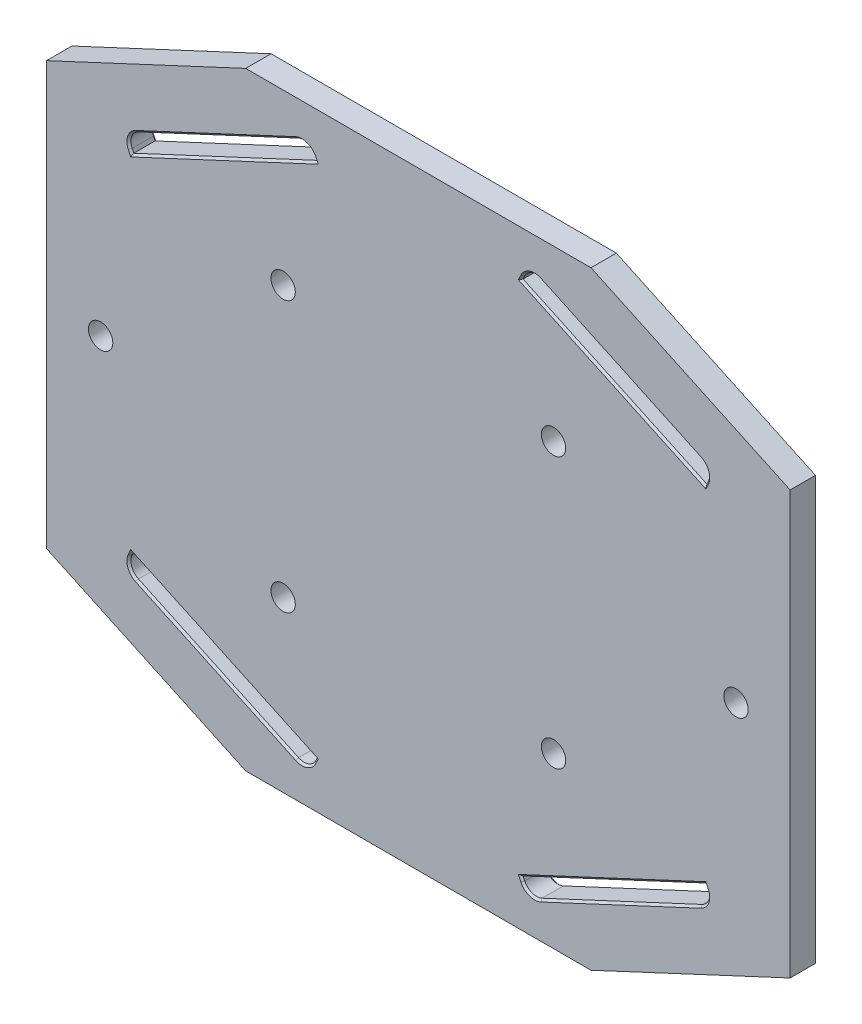
SolidWorks part; units mm, degrees
ref_plane "Front Plane" through (0, 0, 0) normal (0, 0, 1) x (1, 0, 0)
ref_plane "Top Plane" through (0, 0, 0) normal (0, 1, 0) x (1, 0, 0)
ref_plane "Right Plane" through (0, 0, 0) normal (1, 0, 0) x (0, 0, -1)
sketch "Sketch3" plane through (0, 0, 0) normal (0, 0, 1) x (1, 0, 0)
  line L0 (0, 114.3) -> (0, -114.3) construction
  line L1 (64.8681, -114.3) -> (-64.8681, -114.3)
  line L2 (139.7, -79.4053) -> (139.7, 79.4053)
  line L3 (64.8681, 114.3) -> (-64.8681, 114.3)
  line L4 (-139.7, -79.4053) -> (-139.7, 79.4053)
  line L5 (112.5338, -92.0731) -> (-112.5338, 92.0731) construction
  line L6 (112.5338, 92.0731) -> (-112.5338, -92.0731) construction
  line L7 (-9.2742, 114.3) -> (-139.7, 53.4814) construction
  line L8 (-139.7, 0) -> (139.7, 0) construction
  line L9 (9.2742, 114.3) -> (139.7, 53.4814) construction
  line L10 (9.2742, -114.3) -> (139.7, -53.4814) construction
  line L11 (-9.2742, -114.3) -> (-139.7, -53.4814) construction
  line L12 (-107.6756, 64.9114) -> (-38.6149, 97.1149)
  line L13 (-107.6756, 64.9114) -> (-110.3592, 70.6665)
  line L14 (-38.6149, 97.1149) -> (-41.2986, 102.87)
  line L15 (-110.3592, 70.6665) -> (-41.2986, 102.87)
  line L16 (-107.6756, 64.9114) -> (-41.2986, 102.87) construction
  line L17 (-38.6149, 97.1149) -> (-110.3592, 70.6665) construction
  line L18 (-102.284, 96.8526) -> (-74.4871, 83.8907) construction
  line L19 (38.6149, 97.1149) -> (41.2986, 102.87)
  line L20 (110.3592, 70.6665) -> (41.2986, 102.87)
  line L21 (107.6756, 64.9114) -> (110.3592, 70.6665)
  line L22 (107.6756, 64.9114) -> (38.6149, 97.1149)
  line L23 (-38.6149, -97.1149) -> (-41.2986, -102.87)
  line L24 (-110.3592, -70.6665) -> (-41.2986, -102.87)
  line L25 (-107.6756, -64.9114) -> (-110.3592, -70.6665)
  line L26 (-107.6756, -64.9114) -> (-38.6149, -97.1149)
  line L27 (107.6756, -64.9114) -> (38.6149, -97.1149)
  line L28 (107.6756, -64.9114) -> (110.3592, -70.6665)
  line L29 (110.3592, -70.6665) -> (41.2986, -102.87)
  line L30 (38.6149, -97.1149) -> (41.2986, -102.87)
  line L31 (64.8681, 114.3) -> (139.7, 79.4053)
  line L32 (-64.8681, 114.3) -> (-139.7, 79.4053)
  line L33 (64.8681, -114.3) -> (139.7, -79.4053)
  line L34 (-64.8681, -114.3) -> (-139.7, -79.4053)
  line L36 (50.8, -50.8) -> (-50.8, -50.8) construction
  line L37 (50.8, -50.8) -> (50.8, 50.8) construction
  line L38 (50.8, 50.8) -> (-50.8, 50.8) construction
  line L39 (-50.8, -50.8) -> (-50.8, 50.8) construction
  line L40 (50.8, -50.8) -> (-50.8, 50.8) construction
  line L41 (50.8, 50.8) -> (-50.8, -50.8) construction
  circle A0 centre (-50.8, 50.8) radius 4.572
  circle A1 centre (50.8, 50.8) radius 4.572
  circle A2 centre (50.8, -50.8) radius 4.572
  circle A3 centre (-50.8, -50.8) radius 4.572
  circle A4 centre (-119.38, 0) radius 4.572
  circle A5 centre (119.38, 0) radius 4.572
  point P0 (0, 0)
  point P4 (0, 0)
  point P19 (-74.4871, 83.8907)
  point P39 (102.284, 96.8526)
  dimension "D14" = 9.144
  dimension "D15" = 9.144
  dimension "D16" = 9.144
  dimension "D17" = 9.144
  dimension "D18" = 9.144
  dimension "D2" = 279.4
  dimension "D3" = 25
  dimension "D4" = 11.43
  dimension "D5" = 65
  dimension "D6" = 76.2
  dimension "D7" = 6.35
  dimension "D8" = 180
  dimension "D9" = 65
  dimension "D10" = 20.32
  dimension "D11" = 228.6
  dimension "D12" = 101.6
  dimension "D13" = 101.6
  dimension "D19" = 20.32
extrude "Boss-Extrude1" add sketch "Sketch3" along normal blind 9.525
fillet "Fillet1" radius 4.92 1 edges at (-41.2986, 102.87, 4.7625)
fillet "Fillet2" radius 4.92 1 edges at (-110.3592, 70.6665, 4.7625)
chamfer "Chamfer1" distance 0.762 6 edges at (-75.8289, 86.7682, 9.525) (-108.4442, 69.9695, 9.525) (-107.9778, 65.5594, 9.525) (-73.1453, 81.0132, 9.525) (-38.9171, 97.763, 9.525) (-41.9956, 100.955, 9.525)
chamfer "Chamfer2" distance 0.762 6 edges at (-38.9171, 97.763, 0) (-41.9956, 100.955, 0) (-73.1453, 81.0132, 0) (-107.9778, 65.5594, 0) (-108.4442, 69.9695, 0) (-75.8289, 86.7682, 0)
fillet "Fillet3" radius 4.92 1 edges at (41.2986, 102.87, 4.7625)
fillet "Fillet4" radius 4.92 1 edges at (110.3592, 70.6665, 4.7625)
fillet "Fillet5" radius 4.92 1 edges at (110.3592, -70.6665, 4.7625)
fillet "Fillet6" radius 4.92 1 edges at (41.2986, -102.87, 4.7625)
fillet "Fillet7" radius 4.92 1 edges at (-41.2986, -102.87, 4.7625)
fillet "Fillet8" radius 4.92 1 edges at (-110.3592, -70.6665, 4.7625)
chamfer "Chamfer3" distance 0.762 12 edges at (107.9778, 65.5594, 0) (108.4442, 69.9695, 0) (73.1453, 81.0132, 0) (75.8289, 86.7682, 0) (41.9956, 100.955, 0) (38.9171, 97.763, 0) (41.9956, 100.955, 9.525) (38.9171, 97.763, 9.525) (73.1453, 81.0132, 9.525) (107.9778, 65.5594, 9.525) (108.4442, 69.9695, 9.525) (75.8289, 86.7682, 9.525)
chamfer "Chamfer4" distance 0.762 12 edges at (-108.4442, -69.9695, 9.525) (-107.9778, -65.5594, 9.525) (-75.8289, -86.7682, 9.525) (-41.9956, -100.955, 9.525) (-38.9171, -97.763, 9.525) (-73.1453, -81.0132, 9.525) (-73.1453, -81.0132, 0) (-107.9778, -65.5594, 0) (-108.4442, -69.9695, 0) (-75.8289, -86.7682, 0) (-38.9171, -97.763, 0) (-41.9956, -100.955, 0)
chamfer "Chamfer5" distance 0.762 12 edges at (38.9171, -97.763, 9.525) (41.9956, -100.955, 9.525) (75.8289, -86.7682, 9.525) (108.4442, -69.9695, 9.525) (107.9778, -65.5594, 9.525) (73.1453, -81.0132, 9.525) (38.9171, -97.763, 0) (41.9956, -100.955, 0) (75.8289, -86.7682, 0) (108.4442, -69.9695, 0) (107.9778, -65.5594, 0) (73.1453, -81.0132, 0)
